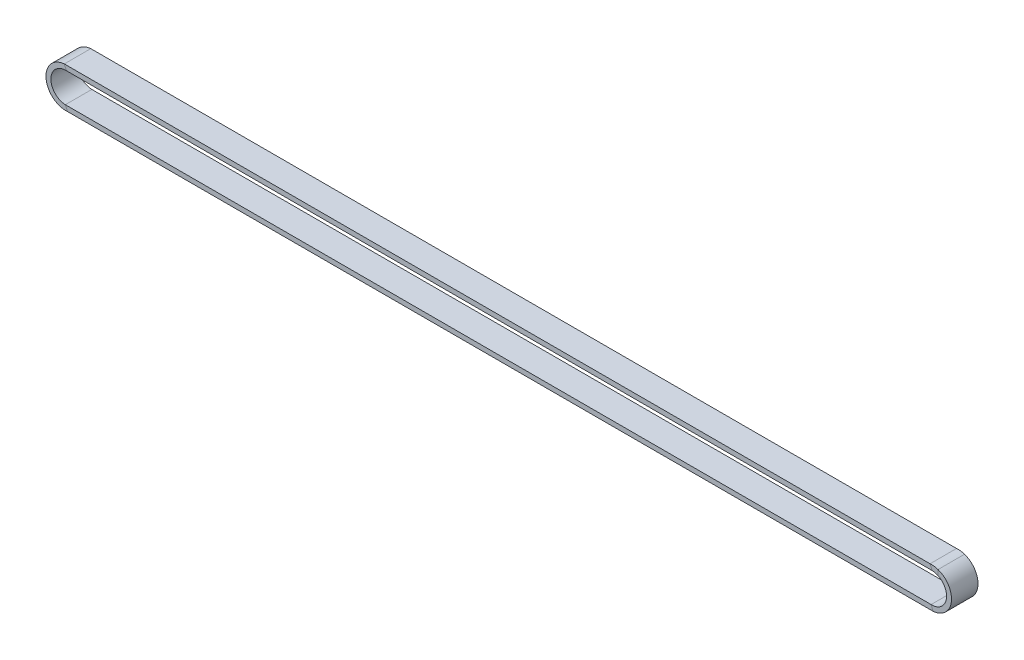
SolidWorks part; units mm, degrees
ref_plane "Front Plane" through (0, 0, 0) normal (0, 0, 1) x (1, 0, 0)
ref_plane "Top Plane" through (0, 0, 0) normal (0, 1, 0) x (1, 0, 0)
ref_plane "Right Plane" through (0, 0, 0) normal (1, 0, 0) x (0, 0, -1)
sketch "Sketch2" plane through (0, 0, 0) normal (0, 0, 1) x (1, 0, 0)
  line L0 (0, 0) -> (1, 0) construction
  line L1 (0, 0) -> (0, 1) construction
  line L2 (-2.4248, 21.3878) -> (-329.4248, 21.3878)
  line L3 (-329.4248, 33.6122) -> (-2.4248, 33.6122)
  arc A0 (-2.4248, 33.6122) -> (-2.4248, 21.3878) centre (-2.4248, 27.5) cw
  arc A1 (-329.4248, 21.3878) -> (-329.4248, 33.6122) centre (-329.4248, 27.5) cw
sketch "Sketch3" plane through (0, 0, 0) normal (1, 0, 0) x (0, 0, -1)
  line L1 (0, 33.6122) -> (0, 21.3878) construction
  line L2 (0, 33.6122) -> (0, 21.3878)
  line L8 (5, 32.6122) -> (-5, 32.6122)
  line L9 (5, 32.6122) -> (5, 34.6122)
  line L10 (5, 34.6122) -> (-5, 34.6122)
  line L11 (-5, 32.6122) -> (-5, 34.6122)
  line L12 (5, 32.6122) -> (-5, 34.6122) construction
  line L13 (5, 34.6122) -> (-5, 32.6122) construction
  dimension "D1" = 10
  dimension "D2" = 2
sweep "Sweep1" add profiles "Sketch3" path "Sketch2"
